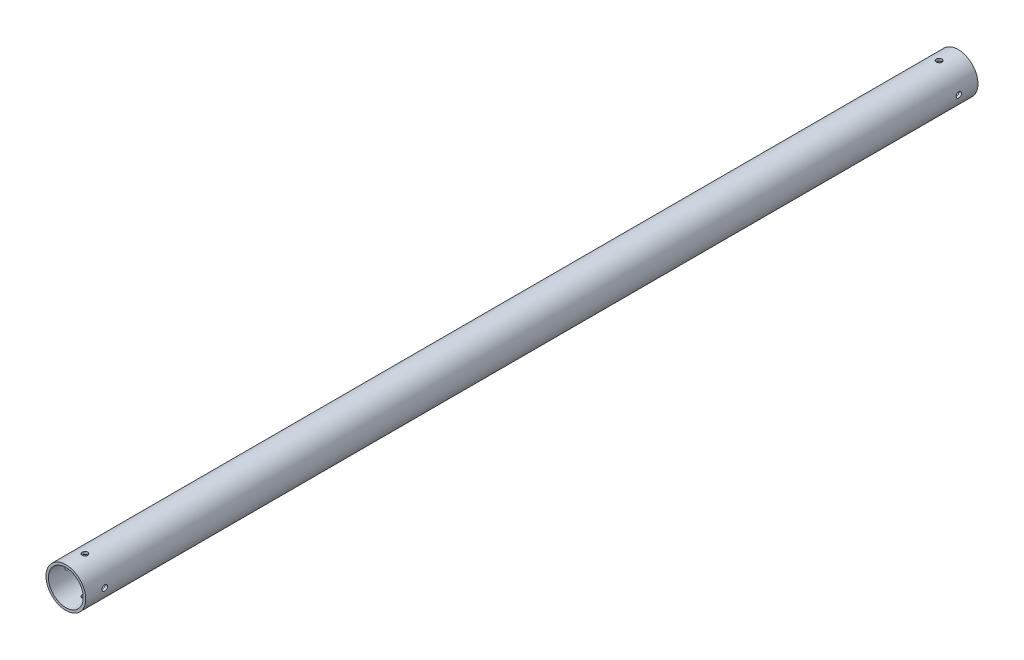
SolidWorks part; units mm, degrees
material "PC High Viscosity"
ref_plane "Front Plane" through (0, 0, 0) normal (0, 0, 1) x (1, 0, 0)
ref_plane "Top Plane" through (0, 0, 0) normal (0, 1, 0) x (1, 0, 0)
ref_plane "Right Plane" through (0, 0, 0) normal (1, 0, 0) x (0, 0, -1)
sketch "Sketch2" plane through (0, 0, 0) normal (0, 0, 1) x (1, 0, 0)
  circle A0 centre (0, 0) radius 11.1125
  circle A1 centre (0, 0) radius 12.7
  dimension "D1" = 25.4
  dimension "D2" = 1.5875
extrude "Boss-Extrude1" add sketch "Sketch2" along normal mid plane 570.1883
sketch "Sketch3" plane through (0, 0, 0) normal (0, 1, 0) x (1, 0, 0)
  line L0 (-12.7, -285.0942) -> (12.7, -285.0942) construction
  line L1 (-55, 0) -> (55, 0) construction
  circle A0 centre (0, -272.9022) radius 1.7526
  circle A1 centre (0, 272.9022) radius 1.7526
  dimension "D1" = 3.5052
  dimension "D2" = 12.192
extrude "Cut-Extrude1" cut sketch "Sketch3" against normal through all both and the other way through all
sketch "Sketch4" plane through (0, 0, 0) normal (1, 0, 0) x (0, 0, -1)
  line L0 (-285.0942, 12.7) -> (-285.0942, -12.7) construction
  line L1 (0, 55) -> (0, -55) construction
  circle A0 centre (-272.9022, 0) radius 1.7526
  circle A1 centre (272.9022, 0) radius 1.7526
  dimension "D1" = 3.5052
  dimension "D2" = 12.192
extrude "Cut-Extrude2" cut sketch "Sketch4" against normal through all both and the other way through all
